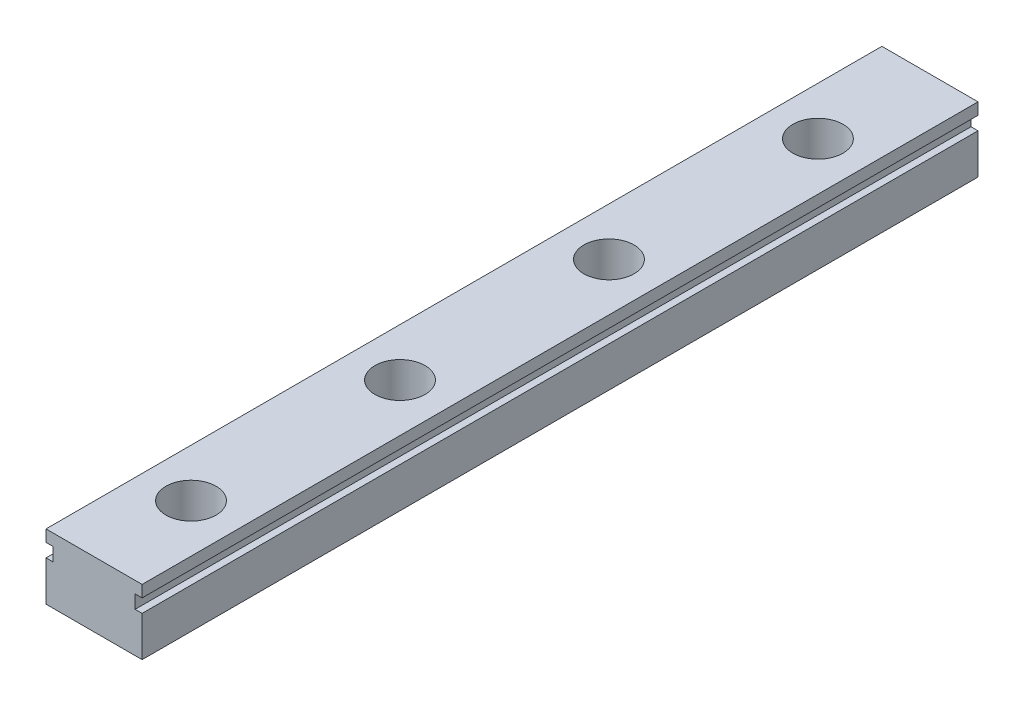
SolidWorks part; units mm, degrees
ref_plane "Front Plane" through (0, 0, 0) normal (0, 0, 1) x (1, 0, 0)
ref_plane "Top Plane" through (0, 0, 0) normal (0, 1, 0) x (1, 0, 0)
ref_plane "Right Plane" through (0, 0, 0) normal (1, 0, 0) x (0, 0, -1)
sketch "Sketch1" plane through (0, 0, 0) normal (0, 0, 1) x (1, 0, 0)
  line L1 (-5.75, -3.9) -> (5.75, -3.9)
  line L2 (-5.75, -3.9) -> (-5.75, 3.9)
  line L3 (-5.75, 3.9) -> (5.75, 3.9)
  line L4 (5.75, -3.9) -> (5.75, 3.9)
  line L5 (-5.75, -3.9) -> (5.75, 3.9) construction
  line L6 (-5.75, 3.9) -> (5.75, -3.9) construction
  point P0 (0, 0)
  dimension "D1" = 11.5
  dimension "D2" = 7.8
extrude "Boss-Extrude1" add sketch "Sketch1" along normal blind 100
sketch "Sketch2" plane through (0, 0, 100) normal (0, 0, 1) x (1, 0, 0)
  line L0 (5.75, -3.9) -> (5.75, 3.9) construction
  line L1 (5.75, 2.5) -> (4.9147, 2.5)
  line L2 (5.75, 2.5) -> (5.75, 0.9)
  line L3 (5.75, 0.9) -> (4.9147, 0.9)
  line L4 (4.9147, 2.5) -> (4.9147, 0.9)
  line L5 (5.75, 3.9) -> (-5.75, 3.9) construction
  line L7 (0, -55) -> (0, 55) construction
  line L8 (-5.75, 0.9) -> (-4.9147, 0.9)
  line L9 (-4.9147, 2.5) -> (-4.9147, 0.9)
  line L10 (-5.75, 2.5) -> (-4.9147, 2.5)
  line L11 (-5.75, 2.5) -> (-5.75, 0.9)
  dimension "D1" = 1.4
  dimension "D2" = 1.6
extrude "Cut-Extrude1" cut sketch "Sketch2" against normal through all
sketch "Sketch3" plane through (0, 3.9, 0) normal (0, 1, 0) x (1, 0, 0)
  line L0 (0, -223.2) -> (0, -215.9183) construction
  line L2 (5.75, -100) -> (-5.75, -100) construction
  circle A0 centre (0, -88.4) radius 3
  circle A1 centre (0, -63.4) radius 3
  circle A2 centre (0, -38.4) radius 3
  circle A3 centre (0, -13.4) radius 3
  circle A4 centre (0, 11.6) radius 3
  circle A5 centre (0, 36.6) radius 3
  circle A6 centre (0, 61.6) radius 3
  circle A7 centre (0, 86.6) radius 3
  circle A8 centre (0, 111.6) radius 3
  circle A9 centre (0, 136.6) radius 3
  circle A10 centre (0, 161.6) radius 3
  circle A11 centre (0, 186.6) radius 3
  circle A12 centre (0, 211.6) radius 3
  circle A13 centre (0, 236.6) radius 3
  circle A14 centre (0, 261.6) radius 3
  circle A15 centre (0, 286.6) radius 3
  circle A16 centre (0, 311.6) radius 3
  circle A17 centre (0, 336.6) radius 3
  circle A18 centre (0, 361.6) radius 3
  circle A19 centre (0, 386.6) radius 3
  circle A20 centre (0, 411.6) radius 3
  circle A21 centre (0, 436.6) radius 3
  circle A22 centre (0, 461.6) radius 3
  circle A23 centre (0, 486.6) radius 3
  circle A24 centre (0, 511.6) radius 3
  dimension "D1" = 11.6
  dimension "D2" = 6
  dimension "D3" = 25
extrude "Cut-Extrude2" cut sketch "Sketch3" against normal blind 4.7
sketch "Sketch4" plane through (0, -0.8, 0) normal (0, 1, 0) x (1, 0, 0)
  circle A0 centre (0, -88.4) radius 1.7
  circle A1 centre (0, -63.4) radius 1.7
  circle A2 centre (0, -38.4) radius 1.7
  circle A3 centre (0, -13.4) radius 1.7
  circle A4 centre (0, 11.6) radius 1.7
  circle A5 centre (0, 36.6) radius 1.7
  circle A6 centre (0, 61.6) radius 1.7
  circle A7 centre (0, 86.6) radius 1.7
  circle A8 centre (0, 111.6) radius 1.7
  circle A9 centre (0, 136.6) radius 1.7
  circle A10 centre (0, 161.6) radius 1.7
  circle A11 centre (0, 186.6) radius 1.7
  circle A12 centre (0, 211.6) radius 1.7
  circle A13 centre (0, 236.6) radius 1.7
  circle A14 centre (0, 261.6) radius 1.7
  circle A15 centre (0, 286.6) radius 1.7
  circle A16 centre (0, 311.6) radius 1.7
  circle A17 centre (0, 336.6) radius 1.7
  circle A18 centre (0, 361.6) radius 1.7
  circle A19 centre (0, 386.6) radius 1.7
  circle A20 centre (0, 411.6) radius 1.7
  circle A21 centre (0, 436.6) radius 1.7
  circle A22 centre (0, 461.6) radius 1.7
  circle A23 centre (0, 486.6) radius 1.7
  circle A24 centre (0, 511.6) radius 1.7
  dimension "D1" = 3.4
  dimension "D2" = 25
extrude "Cut-Extrude3" cut sketch "Sketch4" against normal through all
